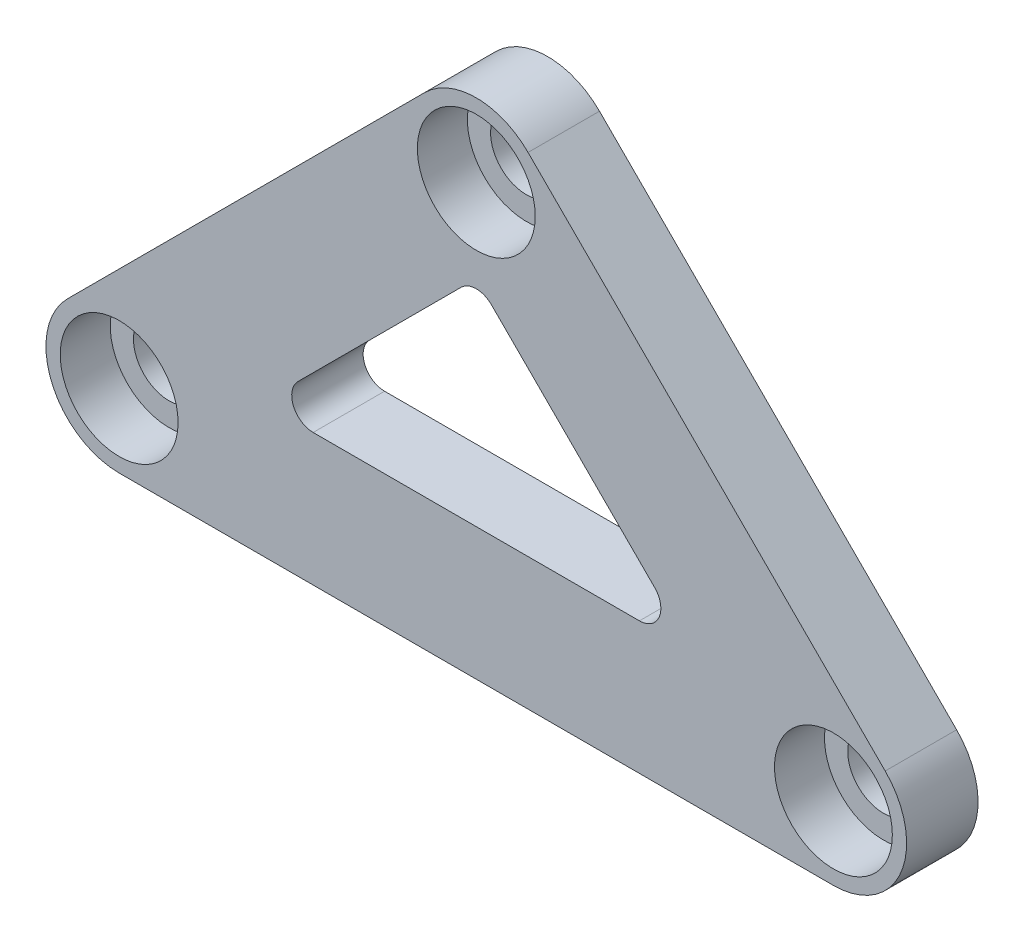
SolidWorks part; units mm, degrees
ref_plane "Front Plane" through (0, 0, 0) normal (0, 0, 1) x (1, 0, 0)
ref_plane "Top Plane" through (0, 0, 0) normal (0, 1, 0) x (1, 0, 0)
ref_plane "Right Plane" through (0, 0, 0) normal (1, 0, 0) x (0, 0, -1)
sketch "Sketch1" plane through (0, 0, 0) normal (0, 0, 1) x (1, 0, 0)
  line L0 (0, 0) -> (100, 0) construction
  line L1 (0, 10.25) -> (100, 10.25)
  line L2 (0, -10.25) -> (100, -10.25)
  line L3 (100, 0) -> (50, 50) construction
  line L4 (92.7522, -7.2478) -> (42.7522, 42.7522)
  line L5 (107.2478, 7.2478) -> (57.2478, 57.2478)
  line L6 (50, 50) -> (0, 0) construction
  line L7 (57.2478, 42.7522) -> (7.2478, -7.2478)
  line L8 (42.7522, 57.2478) -> (-7.2478, 7.2478)
  arc A0 (0, 10.25) -> (0, -10.25) centre (0, 0) ccw
  arc A1 (100, -10.25) -> (100, 10.25) centre (100, 0) ccw
  arc A2 (92.7522, -7.2478) -> (107.2478, 7.2478) centre (100, 0) ccw
  arc A3 (57.2478, 57.2478) -> (42.7522, 42.7522) centre (50, 50) ccw
  arc A4 (57.2478, 42.7522) -> (42.7522, 57.2478) centre (50, 50) ccw
  arc A5 (-7.2478, 7.2478) -> (7.2478, -7.2478) centre (0, 0) ccw
  point P2 (50, 0)
  point P7 (75, 25)
  point P14 (25, 25)
  dimension "D1" = 20.5
  dimension "D2" = 45
  dimension "D3" = 45
  dimension "D4" = 100
extrude "Boss-Extrude1" add sketch "Sketch1" along normal blind 10 contours A4 L7 L4 L1 A1 L5 | L4 A2 A1 L1 | A5 L2 A2 L4 L1 L7
sketch "Sketch2" plane through (0, 0, 10) normal (0, 0, 1) x (1, 0, 0)
  circle A0 centre (50, 50) radius 8.25
  circle A1 centre (100, 0) radius 8.25
  circle A2 centre (0, 0) radius 8.25
  arc A4 (-7.2478, 7.2478) -> (0, -10.25) centre (0, 0) ccw construction
  arc A5 (57.2478, 57.2478) -> (42.7522, 57.2478) centre (50, 50) ccw construction
  arc A6 (100, -10.25) -> (107.2478, 7.2478) centre (100, 0) ccw construction
  dimension "D1" = 16.5
  dimension "D2" = 16.5
  dimension "D3" = 16.5
extrude "Cut-Extrude1" cut sketch "Sketch2" against normal blind 7
sketch "Sketch4" plane through (0, 0, 10) normal (0, 0, 1) x (1, 0, 0)
  line L0 (19.9173, 8.25) -> (80.0827, 8.25)
  line L1 (80.0827, 8.25) -> (50, 38.3327)
  line L2 (50, 38.3327) -> (19.9173, 8.25)
  circle A0 centre (0, 0) radius 8.25 construction
  circle A1 centre (0, 0) radius 8.25 construction
  circle A2 centre (100, 0) radius 8.25 construction
  dimension "D1" = 45
extrude "Cut-Extrude2" cut sketch "Sketch4" against normal blind 16
fillet "Fillet2" radius 3 3 edges at (80.0827, 8.25, 5) (19.9173, 8.25, 5) (50, 38.3327, 5)
sketch "Sketch5" plane through (0, 0, 10) normal (0, 0, 1) x (1, 0, 0)
  circle A0 centre (0, 0) radius 5
  circle A1 centre (50, 50) radius 5
  circle A2 centre (100, 0) radius 5
  circle A3 centre (100, 0) radius 8.25 construction
  circle A4 centre (0, 0) radius 8.25 construction
  circle A5 centre (50, 50) radius 8.25 construction
  dimension "D1" = 10
  dimension "D2" = 10
  dimension "D3" = 10
extrude "Cut-Extrude3" cut sketch "Sketch5" against normal blind 16
equation "\"D3@Sketch1\"=\"D2@Sketch1\""
equation "\"D2@Sketch2\"=\"D1@Sketch2\""
equation "\"D3@Sketch2\"=\"D2@Sketch2\""
equation "\"D2@Sketch5\"=\"D1@Sketch5\""
equation "\"D3@Sketch5\"=\"D1@Sketch5\""
